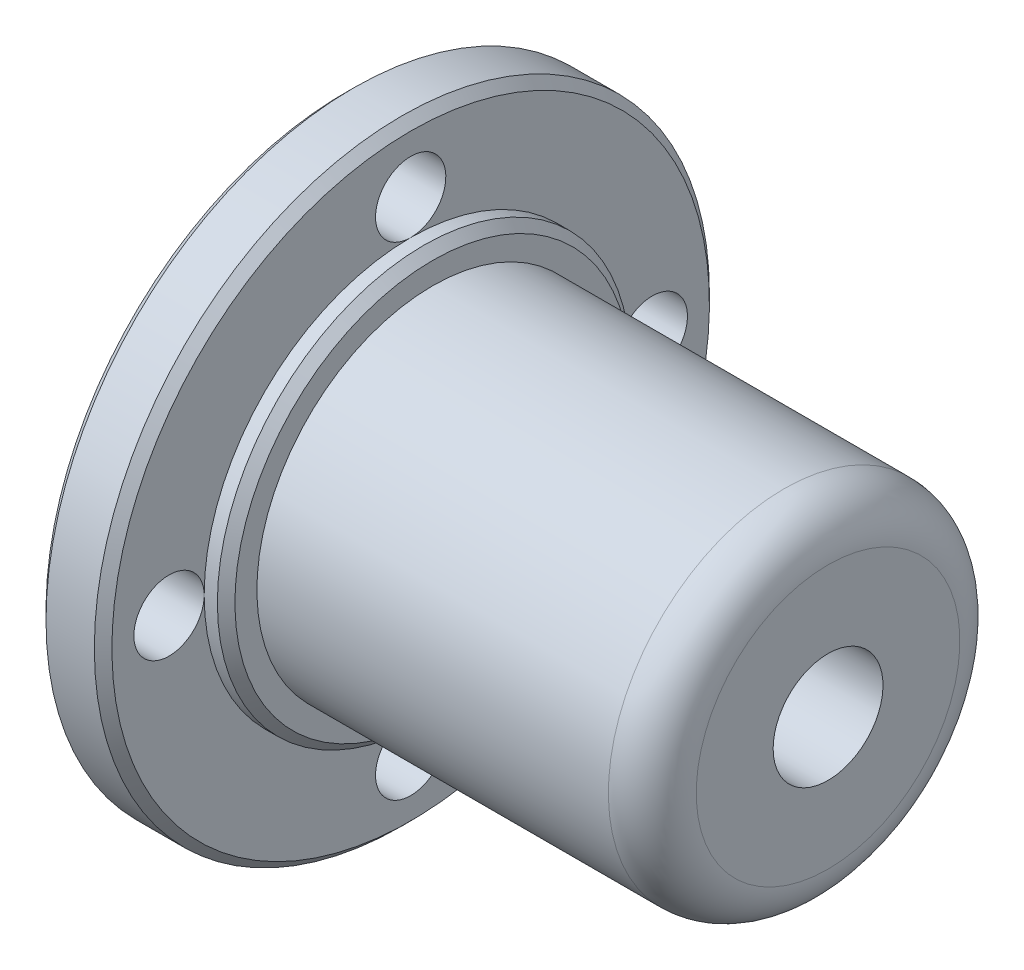
SolidWorks part; units mm, degrees
material "6061-T6 (SS)"
ref_plane "前视基准面" through (0, 0, 0) normal (0, 0, 1) x (1, 0, 0)
ref_plane "上视基准面" through (0, 0, 0) normal (0, 1, 0) x (1, 0, 0)
ref_plane "右视基准面" through (0, 0, 0) normal (1, 0, 0) x (0, 0, -1)
sketch "草图1" plane through (0, 0, 0) normal (0, 0, 1) x (1, 0, 0)
  line L0 (11, 0) -> (6, 0)
  line L1 (6, 0) -> (6, 2.5)
  line L2 (6, 2.5) -> (1, 2.5)
  line L3 (0, 4) -> (0, 7)
  line L4 (1.5, 4.7) -> (2, 4.7)
  line L5 (2, 4.7) -> (2, 4)
  line L6 (2, 4) -> (11, 4)
  line L7 (11, 4) -> (11, 0)
  line L8 (1, 2.5) -> (1, 4)
  line L9 (1, 4) -> (0, 4)
  line L10 (1.5, 4.7) -> (1.5, 7)
  line L11 (1.5, 7) -> (0, 7)
  dimension "D1" = 4
  dimension "D2" = 0.7
  dimension "D3" = 2
  dimension "D4" = 9
  dimension "D5" = 2.5
  dimension "D6" = 6
  dimension "D7" = 7
  dimension "D8" = 0.5
  dimension "D9" = 4
  dimension "D10" = 1
revolve "旋转1" add sketch "草图1" angle 360 about L0
hole_wizard "M3 螺纹孔1" positions "草图2" profile "草图3" tap size "M3" standard "GB" end condition up to next
sketch "草图2" plane through (6, 0, 0) normal (-1, 0, 0) x (0, 0, 1)
  point P0 (0, 0)
sketch "草图3" plane through (6, 0, 0) normal (0, 1, 0) x (0, 0, 1)
  line L0 (0, 0) -> (0, 5)
  line L1 (0, 5) -> (1.25, 5)
  line L2 (1.25, 5) -> (1.25, 0)
  line L5 (1.25, 0) -> (0, 0)
  line L11 (0, -6.35) -> (0, 107.95) construction
  dimension "通孔螺纹孔钻头直径" = 2.5
  dimension "通孔螺纹孔钻头深度" = 5
cosmetic thread "孔螺蚊线1" parameters "D2"=3
fillet "圆角1" radius 1 1 edges at (11, 4, 0)
chamfer "倒角1" distance 0.2 angle 45 4 edges at (1, 2.5, 0) (0, 4, 0) (1.5, 7, 0) (0, 7, 0)
hole_wizard "M2 螺纹孔1" positions "草图4" profile "草图5" tap size "M2" standard "GB" end condition up to next
sketch "草图4" plane through (0, 0, 0) normal (-1, 0, 0) x (0, 0, 1)
  line L0 (0, 0) -> (0, -5.5)
  point P0 (0, -5.5)
  dimension "D1" = 5.5
sketch "草图5" plane through (0, -5.5, 0) normal (0, 1, 0) x (0, 0, 1)
  line L0 (0, 0) -> (0, 1.5)
  line L1 (0, 1.5) -> (0.8, 1.5)
  line L2 (0.8, 1.5) -> (0.8, 0)
  line L5 (0.8, 0) -> (0, 0)
  line L11 (0, -6.35) -> (0, 107.95) construction
  dimension "通孔螺纹孔钻头直径" = 1.6
  dimension "通孔螺纹孔钻头深度" = 1.5
cosmetic thread "孔螺蚊线2" parameters "D2"=2
pattern_circular "阵列(圆周)1" count 4 over 360 about axis through (0, 0, 0) along (1, 0, 0) of "M2 螺纹孔1"
cosmetic thread "孔螺蚊线3" parameters "D2"=2
cosmetic thread "孔螺蚊线4" parameters "D2"=2
cosmetic thread "孔螺蚊线5" parameters "D2"=2
chamfer "倒角2" distance 0.2 angle 45 1 edges at (2, 4.7, 0)
